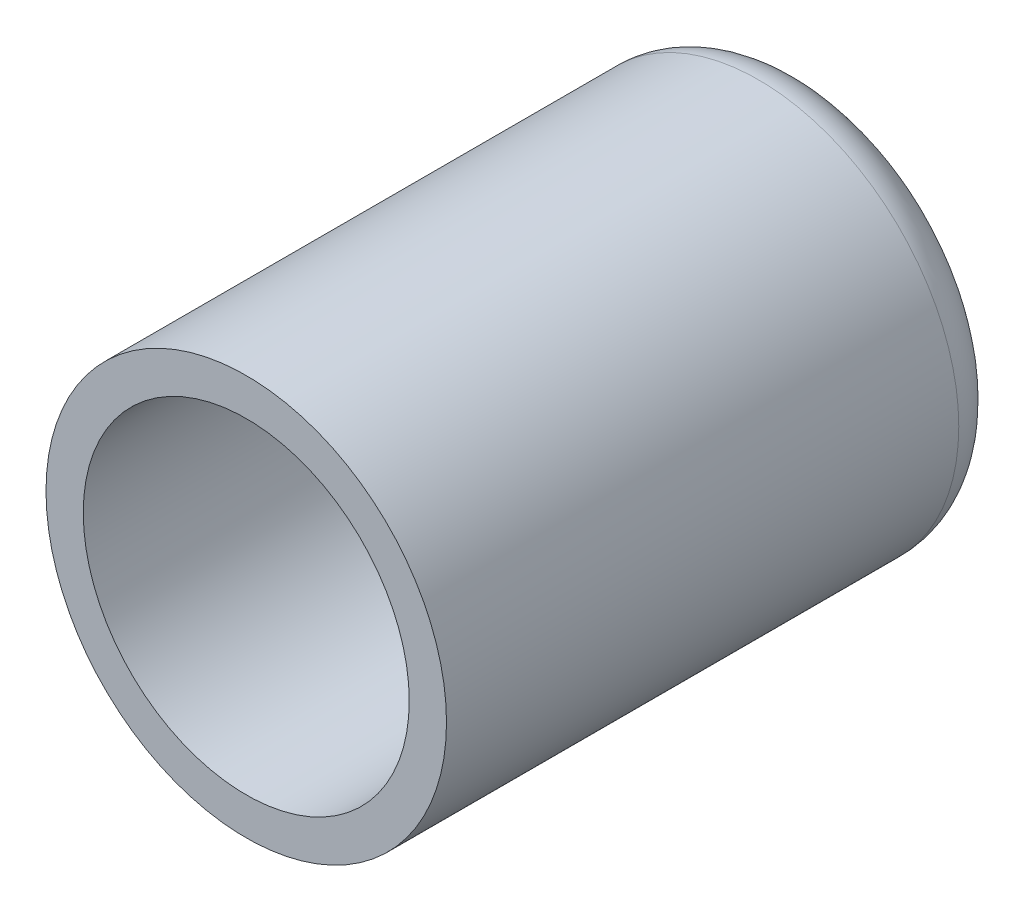
SolidWorks part; units mm, degrees
ref_plane "Front Plane" through (0, 0, 0) normal (0, 0, 1) x (1, 0, 0)
ref_plane "Top Plane" through (0, 0, 0) normal (0, 1, 0) x (1, 0, 0)
ref_plane "Right Plane" through (0, 0, 0) normal (1, 0, 0) x (0, 0, -1)
sketch "Sketch1" plane through (0, 0, 0) normal (0, 0, 1) x (1, 0, 0)
  circle A0 centre (0, 0) radius 2.15
  dimension "D1" = 4.3
extrude "Boss-Extrude1" add sketch "Sketch1" along normal blind 6
sketch "Sketch2" plane through (0, 0, 6) normal (0, 0, 1) x (1, 0, 0)
  circle A0 centre (0, 0) radius 1.75
  circle A1 centre (0, 0) radius 2.15 construction
  dimension "D1" = 0.4
  dimension "D2" = 3.5
extrude "Cut-Extrude1" cut sketch "Sketch2" against normal blind 5.5
fillet "Fillet1" radius 0.5 1 edges at (2.15, 0, 0)
